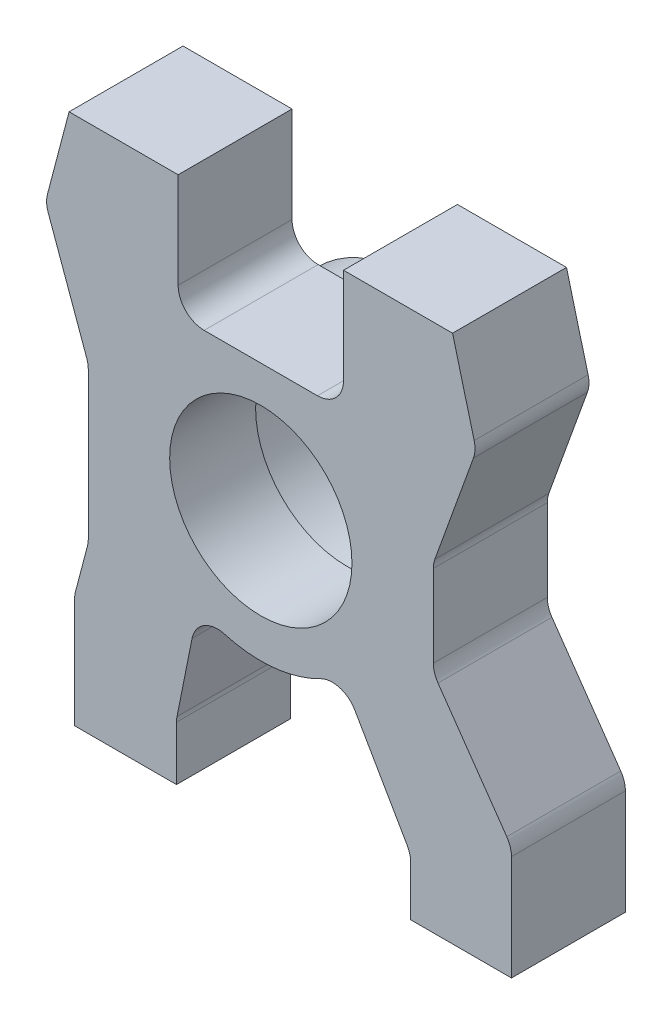
SolidWorks part; units mm, degrees
ref_plane "Front Plane" through (0, 0, 0) normal (0, 0, 1) x (1, 0, 0)
ref_plane "Top Plane" through (0, 0, 0) normal (0, 1, 0) x (1, 0, 0)
ref_plane "Right Plane" through (0, 0, 0) normal (1, 0, 0) x (0, 0, -1)
sketch "Sketch1" plane through (0, 0, 0) normal (0, 0, 1) x (1, 0, 0)
  line L0 (0, 0) -> (0, 36.7423) construction
  line L1 (4.4196, 9.9703) -> (-4.4196, 9.9703)
  line L2 (-6.4516, 12.0023) -> (-6.4516, 19.4699)
  line L3 (-6.4516, 19.4699) -> (-14.9606, 19.4699)
  line L4 (-14.9606, 19.4699) -> (-16.6478, 13.0564)
  line L5 (-16.5939, 11.8494) -> (-13.5828, 3.5095)
  line L6 (-13.462, 2.8194) -> (-13.462, 0)
  line L7 (13.462, 2.8194) -> (13.462, 0)
  line L8 (16.5939, 11.8494) -> (13.5828, 3.5095)
  line L9 (14.9606, 19.4699) -> (16.6478, 13.0564)
  line L10 (6.4516, 19.4699) -> (14.9606, 19.4699)
  line L11 (6.4516, 12.0023) -> (6.4516, 19.4699)
  line L12 (-13.462, 0) -> (-13.462, -8.6478)
  line L13 (-13.5289, -9.1647) -> (-14.4619, -12.7117)
  line L14 (-14.5288, -13.2287) -> (-14.5288, -21.8051)
  line L15 (-14.5288, -21.8051) -> (-6.5786, -21.8051)
  line L16 (-6.5786, -21.8051) -> (-6.5786, -17.587)
  line L17 (-6.539, -17.1879) -> (-5.3634, -11.3177)
  line L18 (7.3426, -9.8251) -> (11.4256, -16.9147)
  line L19 (11.6967, -17.9288) -> (11.6967, -21.8051)
  line L20 (11.6967, -21.8051) -> (19.558, -21.8051)
  line L21 (19.558, -21.8051) -> (19.558, -13.604)
  line L22 (19.1932, -12.4423) -> (13.8268, -4.7399)
  line L23 (13.462, -3.5783) -> (13.462, 0)
  circle A0 centre (0, 0) radius 7.112
  arc A1 (-2.8091, -9.7639) -> (4.6515, -9.0327) centre (0, 0) ccw
  arc A2 (6.4516, 12.0023) -> (4.4196, 9.9703) centre (4.4196, 12.0023) cw
  arc A3 (-4.4196, 9.9703) -> (-6.4516, 12.0023) centre (-4.4196, 12.0023) cw
  arc A4 (16.6478, 13.0564) -> (16.5939, 11.8494) centre (14.6826, 12.5395) cw
  arc A5 (13.5828, 3.5095) -> (13.462, 2.8194) centre (15.494, 2.8194) ccw
  arc A6 (13.462, -3.5783) -> (13.8268, -4.7399) centre (15.494, -3.5783) ccw
  arc A7 (19.1932, -12.4423) -> (19.558, -13.604) centre (17.526, -13.604) cw
  arc A8 (11.6967, -17.9288) -> (11.4256, -16.9147) centre (9.6647, -17.9288) ccw
  arc A9 (7.3426, -9.8251) -> (4.6515, -9.0327) centre (5.5818, -10.8392) ccw
  arc A10 (-2.8091, -9.7639) -> (-5.3634, -11.3177) centre (-3.3709, -11.7167) ccw
  arc A11 (-6.539, -17.1879) -> (-6.5786, -17.587) centre (-4.5466, -17.587) ccw
  arc A12 (-14.5288, -13.2287) -> (-14.4619, -12.7117) centre (-12.4968, -13.2287) cw
  arc A13 (-13.5289, -9.1647) -> (-13.462, -8.6478) centre (-15.494, -8.6478) ccw
  arc A14 (-13.462, 2.8194) -> (-13.5828, 3.5095) centre (-15.494, 2.8194) ccw
  arc A15 (-16.5939, 11.8494) -> (-16.6478, 13.0564) centre (-14.6826, 12.5395) cw
  point P17 (0, 9.9703)
  point P31 (6.4516, 9.9703)
  point P34 (-6.4516, 9.9703)
  point P37 (16.8087, 12.4445)
  point P40 (13.462, 3.175)
  point P43 (13.462, -4.2164)
  point P46 (19.558, -12.9659)
  point P49 (11.6967, -17.3855)
  point P52 (6.2826, -7.9846)
  point P55 (-4.8813, -8.9106)
  point P58 (-6.5786, -17.3855)
  point P61 (-14.5288, -12.9659)
  point P64 (-13.462, -8.9106)
  point P67 (-13.462, 3.175)
  point P70 (-16.8087, 12.4445)
  dimension "D1" = 14.224
  dimension "D10" = 10.16
  dimension "D20" = 2.032
  dimension "D7" = 13.462
  dimension "D2" = 9.4996
  dimension "D3" = 6.4516
  dimension "D4" = 8.509
  dimension "D5" = 7.2644
  dimension "D6" = 3.175
  dimension "D9" = 9.8552
  dimension "D11" = 34.0868
  dimension "D12" = 1.0668
  dimension "D13" = 7.9502
  dimension "D14" = 18.2753
  dimension "D15" = 41.275
  dimension "D16" = 4.2164
  dimension "D17" = 4.4196
  dimension "D18" = 8.8392
  dimension "D19" = 10.8484
extrude "Boss-Extrude1" add sketch "Sketch1" along normal blind 8.89
sketch "Sketch2" plane through (0, 0, 0) normal (0, 0, -1) x (-1, 0, 0)
  line L0 (-1.4212, 9.9703) -> (1.4212, 9.9703)
  line L1 (-4.4196, 9.9703) -> (4.4196, 9.9703) construction
  circle A0 centre (0, 0) radius 8.1026
  arc A1 (-1.4212, 9.9703) -> (1.4212, 9.9703) centre (0, 0) ccw
  dimension "D1" = 16.2052
  dimension "D2" = 20.1422
extrude "Boss-Extrude2" add sketch "Sketch2" along normal blind 2.794
sketch "Sketch4" plane through (0, 0, 0) normal (0, 0, -1) x (-1, 0, 0)
  circle A0 centre (0, 0) radius 8.1026
extrude "Cut-Extrude1" cut sketch "Sketch4" against normal blind 2.1844
sketch "Sketch5" plane through (0, -21.8051, 0) normal (0, -1, 0) x (1, 0, 0)
  line L0 (-14.5288, 4.445) -> (-10.668, 4.445) construction
  line L1 (-14.5288, 8.89) -> (-14.5288, 0) construction
  line L2 (19.558, 4.445) -> (15.6972, 4.445) construction
  line L4 (19.558, 8.89) -> (19.558, 0) construction
  circle A0 centre (-10.668, 4.445) radius 1.4605
  circle A1 centre (15.6972, 4.445) radius 1.4605
  dimension "D1" = 2.921
  dimension "D2" = 26.3652
extrude "Cut-Extrude2" cut sketch "Sketch5" against normal blind 7.62
